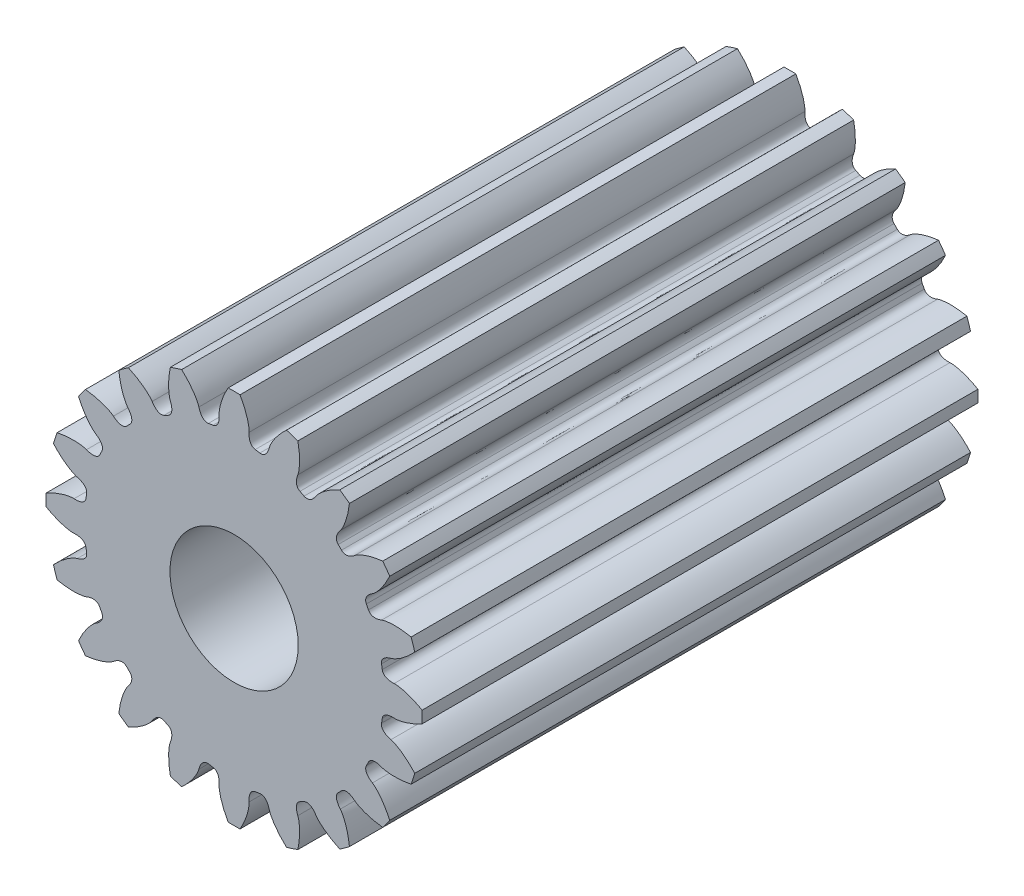
SolidWorks part; units mm, degrees
ref_plane "정면" through (0, 0, 0) normal (0, 0, 1) x (1, 0, 0)
ref_plane "윗면" through (0, 0, 0) normal (0, 1, 0) x (1, 0, 0)
ref_plane "우측면" through (0, 0, 0) normal (1, 0, 0) x (0, 0, -1)
sketch "스케치1" plane through (0, 0, 0) normal (0, 0, 1) x (1, 0, 0)
  circle A0 centre (0, 0) radius 3.5
extrude "돌출1" add sketch "스케치1" along normal blind 13
sketch "스케치2" plane through (0, 0, 0) normal (0, 0, -1) x (-1, 0, 0)
  arc A0 (-0.139, 4.3978) -> (0.139, 4.3978) centre (0, 0)
  arc A1 (-0.4937, 3.465) -> (0.4937, 3.465) centre (0, 0)
  spline S0 degree 3 poles (-0.3508, 3.7437) (-0.351, 3.7494) (-0.3516, 3.7674) (-0.3495, 3.8044) (-0.3427, 3.861) (-0.328, 3.9365) (-0.3027, 4.03) (-0.2641, 4.1402) (-0.2103, 4.2659) (-0.1638, 4.3519) (-0.139, 4.3978) knots 0 0 0 0 0.024662 0.077992 0.15999 0.270656 0.40999 0.577992 0.774662 1 1 1 1
  spline S1 degree 3 poles (0.3508, 3.7437) (0.351, 3.7494) (0.3516, 3.7674) (0.3495, 3.8044) (0.3427, 3.861) (0.328, 3.9365) (0.3027, 4.03) (0.2641, 4.1402) (0.2103, 4.2659) (0.1638, 4.3519) (0.139, 4.3978) knots 0 0 0 0 0.024662 0.077992 0.15999 0.270656 0.40999 0.577992 0.774662 1 1 1 1
  spline S2 degree 3 poles (-0.3508, 3.7437) (-0.3501, 3.7284) (-0.3487, 3.6988) (-0.3512, 3.6558) (-0.3573, 3.6155) (-0.368, 3.5775) (-0.3846, 3.5411) (-0.4096, 3.507) (-0.4459, 3.4772) (-0.4773, 3.4692) (-0.4937, 3.465) knots 0 0 0 0 0.133287 0.257551 0.374687 0.487634 0.600912 0.720919 0.854103 1 1 1 1
  spline S3 degree 3 poles (0.3508, 3.7437) (0.3501, 3.7284) (0.3487, 3.6988) (0.3512, 3.6558) (0.3573, 3.6155) (0.368, 3.5775) (0.3846, 3.5411) (0.4096, 3.507) (0.4459, 3.4772) (0.4773, 3.4692) (0.4937, 3.465) knots 0 0 0 0 0.133287 0.257551 0.374687 0.487634 0.600912 0.720919 0.854103 1 1 1 1
extrude "돌출2" add sketch "스케치2" against normal blind 13
pattern_circular "원형 패턴2" count 20 over 360 about axis through (0, 0, 13) along (0, 0, -1) of "돌출2"
sketch "스케치3" plane through (0, 0, 13) normal (0, 0, 1) x (1, 0, 0)
  circle A0 centre (0, 0) radius 1.5
extrude "컷-돌출1" cut sketch "스케치3" against normal blind 13
